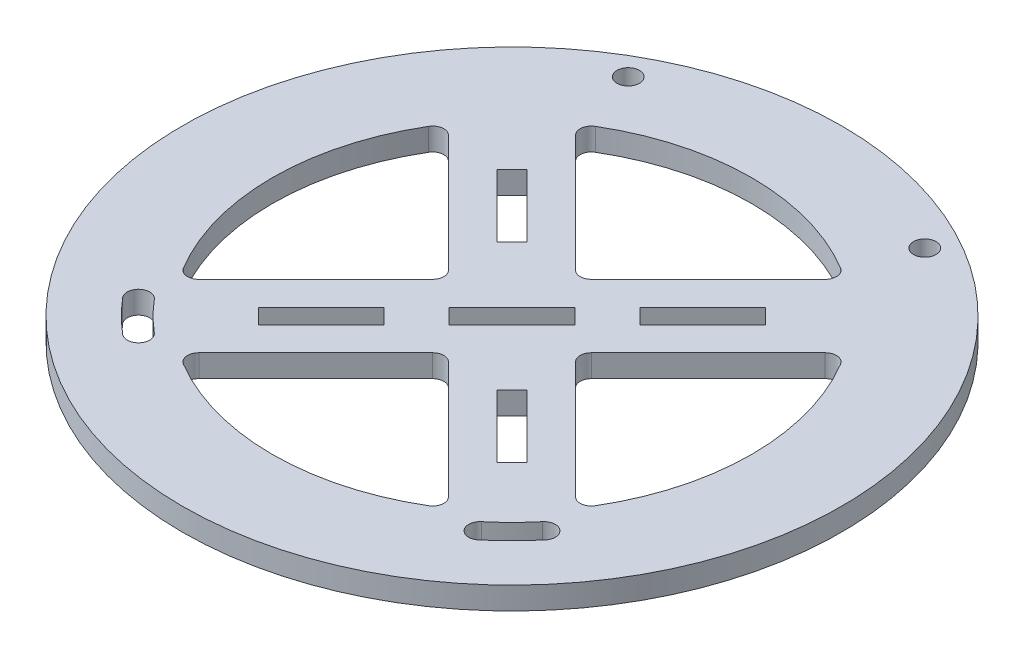
SolidWorks part; units mm, degrees
material "Acrylic (Medium-high impact)"
ref_plane "Front Plane" through (0, 0, 0) normal (0, 0, 1) x (1, 0, 0)
ref_plane "Top Plane" through (0, 0, 0) normal (0, 1, 0) x (1, 0, 0)
ref_plane "Right Plane" through (0, 0, 0) normal (1, 0, 0) x (0, 0, -1)
sketch "Sketch1" plane through (0, 0, 0) normal (0, 1, 0) x (1, 0, 0)
  line L0 (17.6406, -35.3227) -> (1.1225, -18.8046)
  line L1 (-18.9753, 8.1362) -> (-16.838, 10.2735)
  line L2 (26.6208, -26.3424) -> (10.1028, -9.8244)
  line L3 (-7.9655, 1.401) -> (-16.838, 10.2735)
  line L4 (-26.6208, -26.3424) -> (-10.1028, -9.8244)
  line L5 (-10.1028, -0.7363) -> (-7.9655, 1.401)
  line L6 (-10.1028, -0.7363) -> (-18.9753, 8.1362)
  line L7 (-18.9753, -25.5398) -> (-10.1028, -16.6673)
  line L8 (-17.6406, -35.3227) -> (-1.1225, -18.8046)
  line L12 (-7.9655, -18.8046) -> (-10.1028, -16.6673)
  line L13 (-16.838, -27.6771) -> (-7.9655, -18.8046)
  line L16 (-16.838, -27.6771) -> (-18.9753, -25.5398)
  line L19 (-5.5049, -12.0694) -> (3.3676, -3.1969)
  line L20 (5.5049, -5.3342) -> (3.3676, -3.1969)
  line L22 (-3.3676, -14.2067) -> (5.5049, -5.3342)
  line L24 (-3.3676, -14.2067) -> (-5.5049, -12.0694)
  line L25 (7.9655, 1.401) -> (16.838, 10.2735)
  line L26 (18.9753, 8.1362) -> (16.838, 10.2735)
  line L27 (10.1028, -0.7363) -> (18.9753, 8.1362)
  line L29 (10.1028, -0.7363) -> (7.9655, 1.401)
  line L30 (7.9655, -18.8046) -> (10.1028, -16.6673)
  line L31 (18.9753, -25.5398) -> (10.1028, -16.6673)
  line L32 (16.838, -27.6771) -> (18.9753, -25.5398)
  line L33 (16.838, -27.6771) -> (7.9655, -18.8046)
  line L49 (10.1028, -7.5793) -> (26.6208, 8.9388)
  line L51 (-1.1225, 1.401) -> (-17.6406, 17.919)
  line L52 (1.1225, 1.401) -> (17.6406, 17.919)
  line L54 (-10.1028, -7.5793) -> (-26.6208, 8.9388)
  circle A0 centre (0, -8.7018) radius 46.5759
  arc A1 (-17.3302, -37.8092) -> (17.3302, -37.8092) centre (0, -8.7018) ccw
  arc A2 (29.1074, -26.032) -> (29.1074, 8.6284) centre (0, -8.7018) ccw
  arc A3 (-29.7625, -33.9665) -> (-27.342, -31.9118) centre (-28.5523, -32.9392) cw
  circle A4 centre (-21.0623, 28.7859) radius 1.5875
  circle A5 centre (20.8477, 28.7859) radius 1.5875
  arc A6 (23.0006, -36.0394) -> (25.0447, -38.4688) centre (24.0227, -37.2541) ccw
  arc A7 (-25.2647, -38.4643) -> (-23.21, -36.0438) centre (-24.2373, -37.2541) ccw
  arc A8 (27.3375, -31.7024) -> (29.767, -33.7465) centre (28.5523, -32.7245) cw
  arc A9 (17.3302, 20.4056) -> (-17.3302, 20.4056) centre (0, -8.7018) ccw
  arc A10 (-29.1074, 8.6284) -> (-29.1074, -26.032) centre (0, -8.7018) ccw
  arc A11 (-29.7625, -33.9665) -> (-25.2647, -38.4643) centre (0, -8.7018) ccw
  arc A12 (-27.342, -31.9118) -> (-23.21, -36.0438) centre (0, -8.7018) ccw
  arc A13 (25.0447, -38.4688) -> (29.767, -33.7465) centre (0, -8.7018) ccw
  arc A14 (23.0006, -36.0394) -> (27.3375, -31.7024) centre (0, -8.7018) ccw
  arc A16 (26.6208, 8.9388) -> (29.1074, 8.6284) centre (27.7434, 7.8162) cw
  arc A17 (26.6208, -26.3424) -> (29.1074, -26.032) centre (27.7434, -25.2199) ccw
  arc A21 (10.1028, -7.5793) -> (10.1028, -9.8244) centre (11.2253, -8.7018) ccw
  arc A22 (17.6406, 17.919) -> (17.3302, 20.4056) centre (16.5181, 19.0416) ccw
  arc A28 (-1.1225, 1.401) -> (1.1225, 1.401) centre (0, 2.5235) ccw
  arc A29 (-17.6406, 17.919) -> (-17.3302, 20.4056) centre (-16.5181, 19.0416) cw
  arc A31 (-26.6208, 8.9388) -> (-29.1074, 8.6284) centre (-27.7434, 7.8162) ccw
  arc A40 (-10.1028, -9.8244) -> (-10.1028, -7.5793) centre (-11.2253, -8.7018) ccw
  arc A41 (-26.6208, -26.3424) -> (-29.1074, -26.032) centre (-27.7434, -25.2199) cw
  arc A42 (1.1225, -18.8046) -> (-1.1225, -18.8046) centre (0, -19.9271) ccw
  arc A43 (17.6406, -35.3227) -> (17.3302, -37.8092) centre (16.5181, -36.4452) cw
  arc A44 (-17.6406, -35.3227) -> (-17.3302, -37.8092) centre (-16.5181, -36.4452) ccw
  point P6 (28.0194, 10.3373)
  point P13 (28.0194, -27.741)
  point P29 (19.0392, 19.3176)
  point P41 (0, 0.2784)
  point P46 (-19.0392, 19.3176)
  point P57 (-28.0194, 10.3373)
  point P66 (-8.9803, -8.7018)
  point P106 (0, -8.7018)
extrude "Boss-Extrude1" add sketch "Sketch1" along normal blind 3.175
